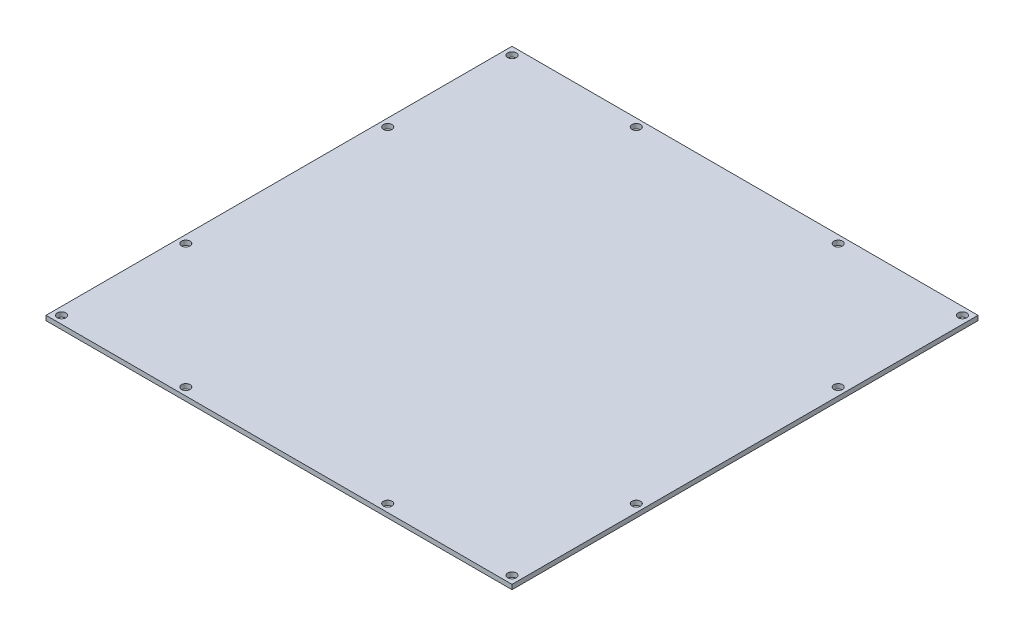
SolidWorks part; units mm, degrees
ref_plane "Front Plane" through (0, 0, 0) normal (0, 0, 1) x (1, 0, 0)
ref_plane "Top Plane" through (0, 0, 0) normal (0, 1, 0) x (1, 0, 0)
ref_plane "Right Plane" through (0, 0, 0) normal (1, 0, 0) x (0, 0, -1)
sketch "Sketch1" plane through (0, 0, 0) normal (0, 1, 0) x (1, 0, 0)
  line L1 (-150, 150) -> (150, 150)
  line L2 (-150, 150) -> (-150, -150)
  line L3 (-150, -150) -> (150, -150)
  line L4 (150, 150) -> (150, -150)
  line L5 (-150, 150) -> (150, -150) construction
  line L6 (-150, -150) -> (150, 150) construction
  point P0 (0, 0)
  dimension "D1" = 300
  dimension "D2" = 300
extrude "Boss-Extrude1" add sketch "Sketch1" along normal blind 3
sketch "Sketch2" plane through (0, 3, 0) normal (0, 1, 0) x (1, 0, 0)
  line L0 (150, 150) -> (-150, 150) construction
  line L1 (-145, 145) -> (145, 145) construction
  line L2 (-145, 145) -> (-145, -145) construction
  line L3 (-145, -145) -> (145, -145) construction
  line L4 (145, 145) -> (145, -145) construction
  line L5 (-150, 150) -> (-150, -150) construction
  line L6 (150, -150) -> (150, 150) construction
  line L7 (-150, -150) -> (150, -150) construction
  line L8 (65, 145) -> (-65, 145)
  line L10 (-65, -145) -> (65, -145)
  line L12 (-145, -65) -> (-145, 65)
  line L14 (145, -65) -> (145, 65)
  point P0 (-145, 145)
  point P1 (145, -145)
  point P2 (-145, -145)
  point P3 (145, 145)
  point P18 (-65, 145)
  point P43 (65, 145)
  point P44 (0, 145)
  point P48 (65, -145)
  point P58 (-65, -145)
  point P59 (0, -145)
  point P62 (-145, 65)
  point P76 (-145, -65)
  point P77 (-145, 0)
  point P81 (145, 65)
  point P110 (145, -65)
  point P111 (145, 0)
  dimension "D1" = 5
  dimension "D2" = 5
  dimension "D3" = 5
  dimension "D4" = 5
  dimension "D5" = 80
  dimension "D6" = 80
  dimension "D7" = 80
  dimension "D8" = 80
hole_wizard "M5 Clearance Hole1" positions "Sketch2" profile "Sketch3" hole size "M5" standard "ANSI Metric"
sketch "Sketch3" plane through (-145, 3, -145) normal (1, 0, 0) x (0, 0, 1)
  line L0 (0, 0) -> (0, 11.6524)
  line L1 (0, 11.6524) -> (2.75, 10)
  line L2 (2.75, 10) -> (2.75, 0)
  line L5 (2.75, 0) -> (0, 0)
  line L10 (0, 11.6524) -> (-2.75, 10) construction
  line L11 (0, -6.35) -> (0, 107.95) construction
  dimension "Hole Dia." = 5.5
  dimension "Hole Depth" = 10
  dimension "Drill Angle" = 118
